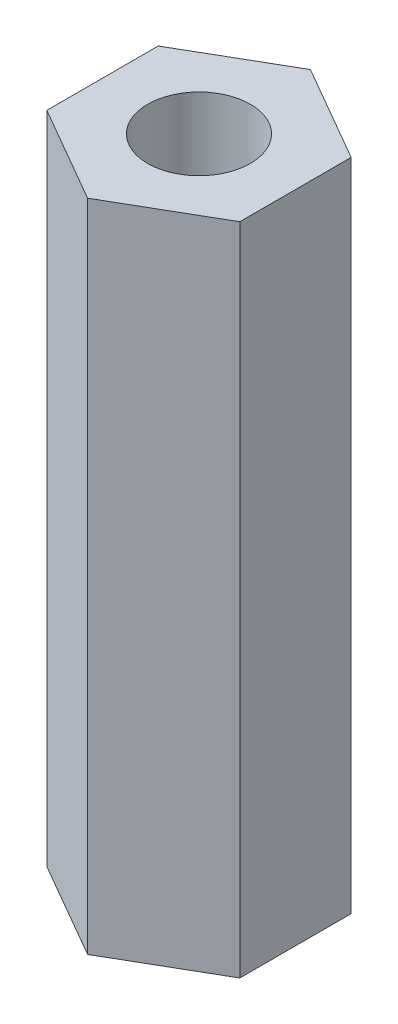
SolidWorks part; units mm, degrees
ref_plane "Přední rovina" through (0, 0, 0) normal (0, 0, 1) x (1, 0, 0)
ref_plane "Horní rovina" through (0, 0, 0) normal (0, 1, 0) x (1, 0, 0)
ref_plane "Pravá rovina" through (0, 0, 0) normal (1, 0, 0) x (0, 0, -1)
sketch "Sketch1" plane through (0, 0, 0) normal (0, 1, 0) x (1, 0, 0)
  line L0 (0, 3.1466) -> (0, 0) construction
  line L1 (0, 3.1466) -> (-2.725, 1.5733)
  line L2 (-2.725, 1.5733) -> (-2.725, -1.5733)
  line L3 (-2.725, -1.5733) -> (0, -3.1466)
  line L4 (0, -3.1466) -> (2.725, -1.5733)
  line L5 (2.725, -1.5733) -> (2.725, 1.5733)
  line L6 (2.725, 1.5733) -> (0, 3.1466)
  circle A0 centre (0, 0) radius 2.725 construction
  circle A1 centre (0, 0) radius 1.45
  dimension "D1" = 2.9
  dimension "D2" = 5.45
extrude "Boss-Extrude1" add sketch "Sketch1" along normal blind 18.5
